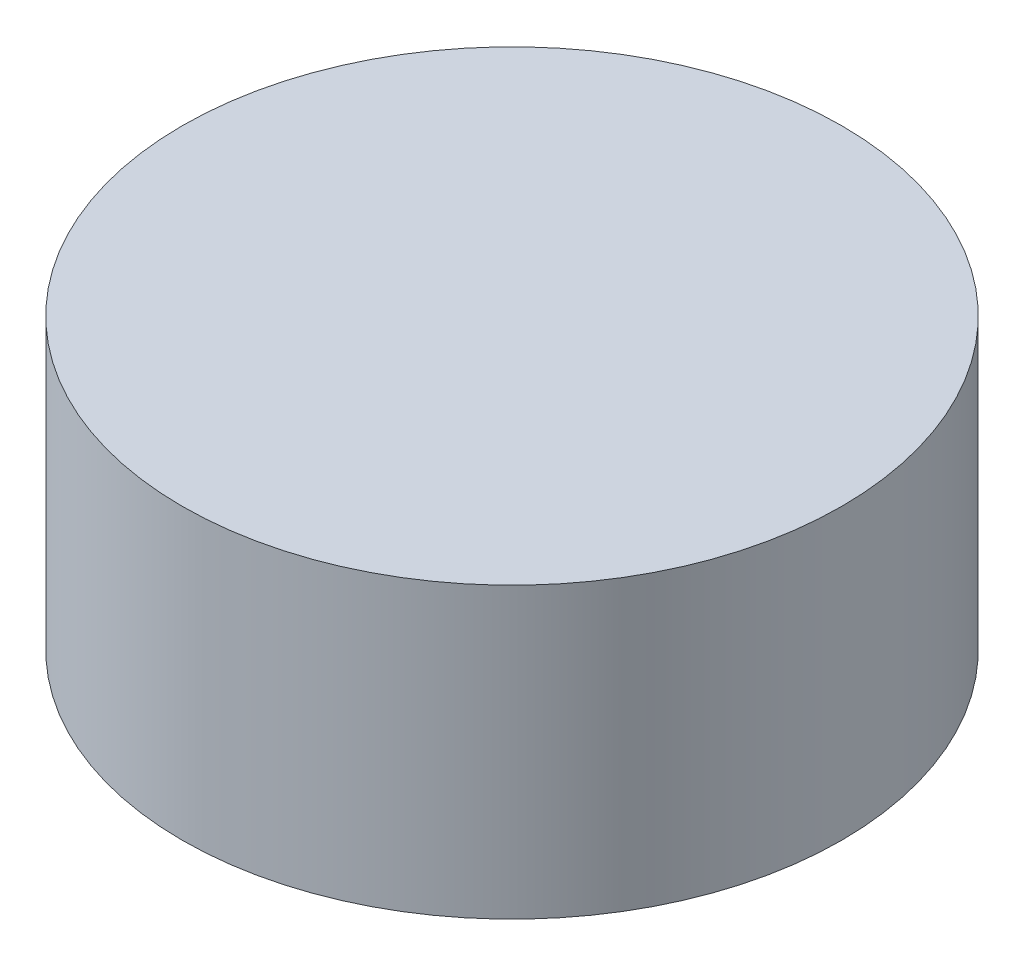
SolidWorks part; units mm, degrees
ref_plane "Front Plane" through (0, 0, 0) normal (0, 0, 1) x (1, 0, 0)
ref_plane "Top Plane" through (0, 0, 0) normal (0, 1, 0) x (1, 0, 0)
ref_plane "Right Plane" through (0, 0, 0) normal (1, 0, 0) x (0, 0, -1)
sketch "Sketch1" plane through (0, 0, 0) normal (0, 1, 0) x (1, 0, 0)
  circle A0 centre (0, 0) radius 2.85
  dimension "D1" = 5.7
extrude "Boss-Extrude1" add sketch "Sketch1" along normal blind 2.5
